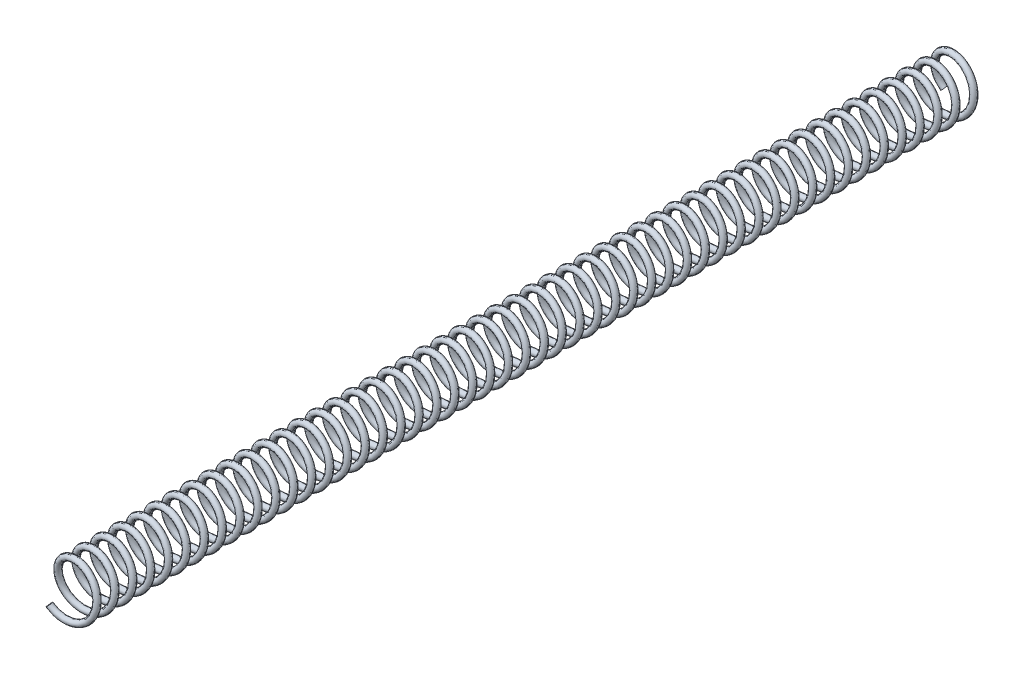
SolidWorks part; units mm, degrees
ref_plane "Front Plane" through (0, 0, 0) normal (0, 0, 1) x (1, 0, 0)
ref_plane "Top Plane" through (0, 0, 0) normal (0, 1, 0) x (1, 0, 0)
ref_plane "Right Plane" through (0, 0, 0) normal (1, 0, 0) x (0, 0, -1)
sketch "Sketch3" plane through (0, 0, 0) normal (0, 0, 1) x (1, 0, 0)
  circle A0 centre (0, 0) radius 4
  dimension "D1" = 8
curve "Helix/Spiral2" pitch 3 height 150 turns 50
sweep "Sweep1" add path "Helix/Spiral2" circular profile diameter 1 parameters "D3"=1
ref_plane "Plane1" through (0, 0, 1.5) normal (0, 0, 1) x (1, 0, 0)
